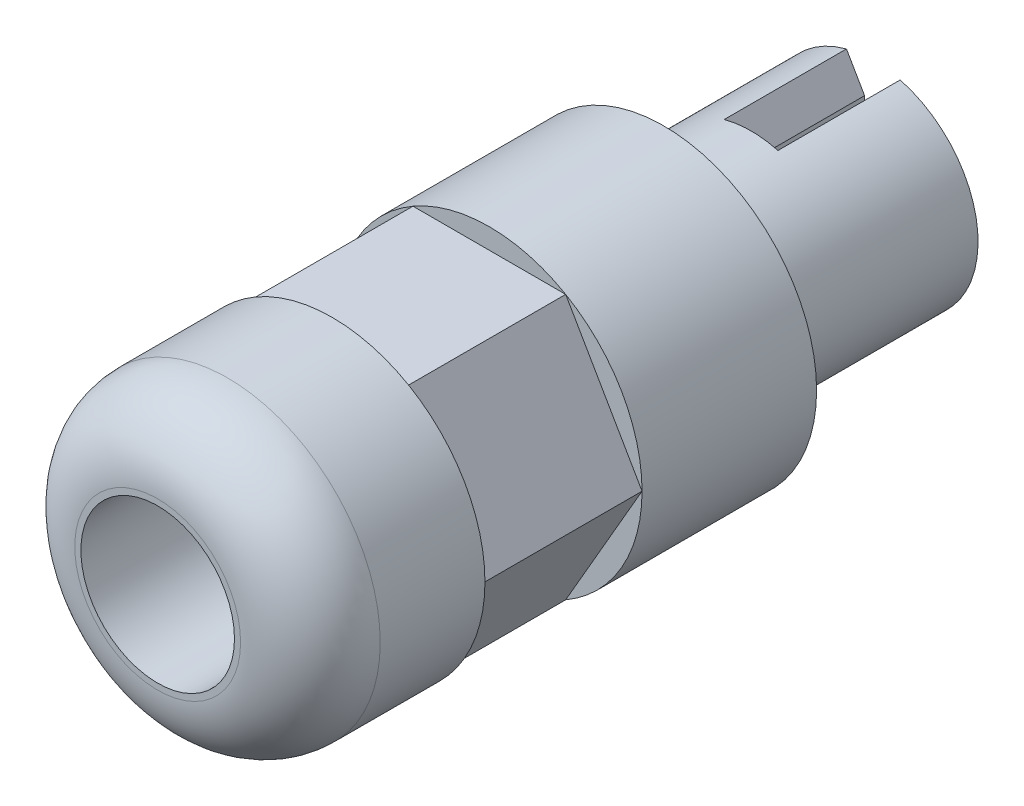
SolidWorks part; units mm, degrees
ref_plane "Front Plane" through (0, 0, 0) normal (0, 0, 1) x (1, 0, 0)
ref_plane "Top Plane" through (0, 0, 0) normal (0, 1, 0) x (1, 0, 0)
ref_plane "Right Plane" through (0, 0, 0) normal (1, 0, 0) x (0, 0, -1)
sketch "Sketch1" plane through (0, 0, 0) normal (0, 0, 1) x (1, 0, 0)
  circle A0 centre (0, 0) radius 6
  dimension "D1" = 12
extrude "Boss-Extrude1" add sketch "Sketch1" along normal blind 12
sketch "Sketch2" plane through (0, 0, 12) normal (0, 0, 1) x (1, 0, 0)
  circle A0 centre (0, 0) radius 8.75
  dimension "D1" = 17.5
extrude "Boss-Extrude2" add sketch "Sketch2" along normal blind 10
sketch "Sketch3" plane through (0, 0, 22) normal (0, 0, 1) x (1, 0, 0)
  line L1 (4.375, 7.5777) -> (-4.375, 7.5777)
  line L2 (-4.375, 7.5777) -> (-8.75, 0)
  line L3 (-8.75, 0) -> (-4.375, -7.5777)
  line L4 (-4.375, -7.5777) -> (4.375, -7.5777)
  line L5 (4.375, -7.5777) -> (8.75, 0)
  line L6 (8.75, 0) -> (4.375, 7.5777)
  circle A0 centre (0, 0) radius 7.5777 construction
extrude "Boss-Extrude3" add sketch "Sketch3" along normal blind 9
sketch "Sketch4" plane through (0, 0, 31) normal (0, 0, 1) x (1, 0, 0)
  circle A0 centre (0, 0) radius 8.75
extrude "Boss-Extrude4" add sketch "Sketch4" along normal blind 10
fillet "Fillet1" radius 4 1 edges at (8.75, 0, 41)
sketch "Sketch5" plane through (0, 0, 41) normal (0, 0, 1) x (1, 0, 0)
  circle A0 centre (0, 0) radius 4.4
  dimension "D1" = 8.8
extrude "Cut-Extrude1" cut sketch "Sketch5" against normal blind 20
sketch "Sketch6" plane through (0, 0, 0) normal (0, 0, -1) x (-1, 0, 0)
  line L0 (0, 6) -> (0, -6) construction
  line L1 (-0.5, -5.9791) -> (-0.5, 4)
  line L2 (-0.5, 4) -> (-1.5388, 5.7993)
  line L3 (0.5, 4) -> (1.5388, 5.7993)
  line L4 (0.5, -5.9791) -> (0.5, 4)
  circle A0 centre (0, 0) radius 6 construction
  circle A1 centre (0, 0) radius 6 construction
  arc A2 (-0.5, -5.9791) -> (0.5, -5.9791) centre (0, 0) ccw
  arc A3 (1.5388, 5.7993) -> (-1.5388, 5.7993) centre (0, 0) ccw
  dimension "D1" = 0.5
  dimension "D2" = 30
  dimension "D3" = 2
extrude "Cut-Extrude2" cut sketch "Sketch6" against normal blind 7
sketch "Sketch7" plane through (0, 0, 0) normal (0, 0, -1) x (-1, 0, 0)
  circle A0 centre (-2.5, 0) radius 1
  circle A1 centre (2.5, 0) radius 1
  dimension "D3" = 2
  dimension "D4" = 2
  dimension "D1" = 2.5
  dimension "D2" = 2.5
extrude "Cut-Extrude3" cut sketch "Sketch7" against normal blind 7
chamfer "Chamfer1" distance 0.2 angle 45 2 edges at (-3.5, 0, 0) (1.5, 0, 0)
